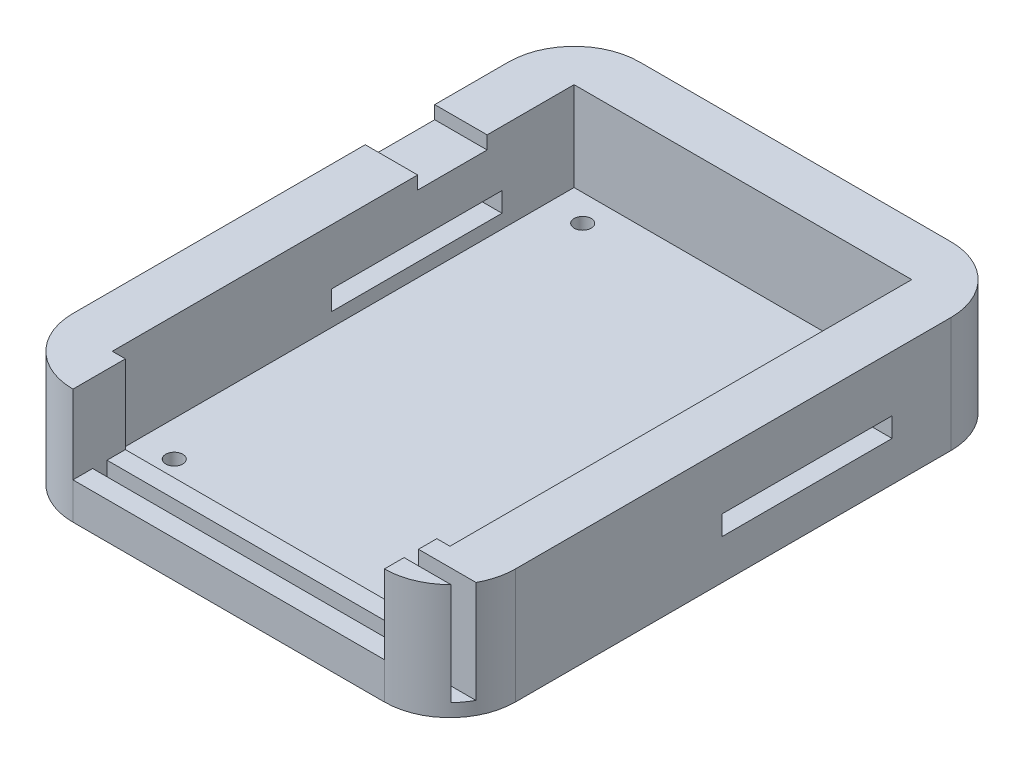
SolidWorks part; units mm, degrees
ref_plane "前视基准面" through (0, 0, 0) normal (0, 0, 1) x (1, 0, 0)
ref_plane "上视基准面" through (0, 0, 0) normal (0, 1, 0) x (1, 0, 0)
ref_plane "右视基准面" through (0, 0, 0) normal (1, 0, 0) x (0, 0, -1)
other "Configuration Table"
sketch "草图1" plane through (0, 0, 0) normal (0, 1, 0) x (1, 0, 0)
  line L0 (0, 0) -> (0, 48.9994) construction
  line L1 (-25.775, -35.25) -> (25.775, -35.25)
  line L2 (-25.775, -35.25) -> (-25.775, 35.25)
  line L3 (-25.775, 35.25) -> (25.775, 35.25)
  line L4 (25.775, -35.25) -> (25.775, 35.25)
  line L5 (-25.775, -35.25) -> (25.775, 35.25) construction
  line L6 (-25.775, 35.25) -> (25.775, -35.25) construction
  line L7 (0, 0) -> (56.532, 0) construction
  circle A0 centre (-20.3835, 31.1785) radius 1.3
  circle A1 centre (20.3835, 31.1785) radius 1.3
  circle A2 centre (20.3835, -31.1785) radius 1.3
  circle A3 centre (-20.3835, -31.1785) radius 1.3
  point P0 (0, 0)
  dimension "D5" = 2.6
  dimension "D1" = 51.55
  dimension "D2" = 70.5
  dimension "D3" = 40.767
  dimension "D4" = 62.357
extrude "凸台-拉伸1" add sketch "草图1" along normal blind 4
sketch "草图2" plane through (0, 0, 0) normal (0, -1, 0) x (1, 0, 0)
  line L0 (-25.775, 35.25) -> (25.775, 35.25) construction
  line L1 (25.775, 35.25) -> (25.775, -35.25) construction
  line L2 (25.775, -35.25) -> (-25.775, -35.25) construction
  line L3 (-25.775, -35.25) -> (-25.775, 35.25) construction
  line L4 (-25.775, 35.25) -> (25.775, 35.25)
  line L5 (25.775, 35.25) -> (25.775, -35.25)
  line L6 (25.775, -35.25) -> (-25.775, -35.25)
  line L7 (-25.775, -35.25) -> (-25.775, 35.25)
  line L9 (-23.775, 43.25) -> (23.775, 43.25)
  line L10 (-33.775, 33.25) -> (-33.775, -33.25)
  line L11 (-23.775, -43.25) -> (23.775, -43.25)
  line L12 (33.775, 33.25) -> (33.775, -33.25)
  line L13 (-33.775, 43.25) -> (33.775, -43.25) construction
  line L14 (-33.775, -43.25) -> (33.775, 43.25) construction
  arc A0 (-23.775, -43.25) -> (-33.775, -33.25) centre (-23.775, -33.25) cw
  arc A1 (23.775, -43.25) -> (33.775, -33.25) centre (23.775, -33.25) ccw
  arc A2 (33.775, 33.25) -> (23.775, 43.25) centre (23.775, 33.25) ccw
  arc A3 (-33.775, 33.25) -> (-23.775, 43.25) centre (-23.775, 33.25) cw
  point P2 (0, 0)
  dimension "D3" = 10
  dimension "D1" = 8
  dimension "D2" = 8
extrude "凸台-拉伸2" add sketch "草图2" against normal blind 17.6
sketch "草图4" plane through (0, 17.6, 0) normal (0, 1, 0) x (1, 0, 0)
  line L0 (25.775, -35.25) -> (-25.775, -35.25) construction
  line L1 (23.775, -43.25) -> (-23.775, -43.25)
  line L2 (23.775, -43.25) -> (23.775, -35.25)
  line L3 (23.775, -35.25) -> (-23.775, -35.25)
  line L4 (-23.775, -43.25) -> (-23.775, -35.25)
  line L5 (23.775, -43.25) -> (-23.775, -43.25) construction
extrude "切除-拉伸1" cut sketch "草图4" against normal blind 12
ref_plane "基准面1" through (0, 0, 38.05) normal (0, 0, -1) x (-1, 0, 0)
sketch "草图6" plane through (0, 0, 38.05) normal (0, 0, -1) x (-1, 0, 0)
  line L0 (25.775, 4) -> (-25.775, 4) construction
  line L1 (23.775, 17.6) -> (-33.775, 17.6)
  line L2 (23.775, 17.6) -> (23.775, 2)
  line L3 (23.775, 2) -> (-33.775, 2)
  line L4 (-33.775, 17.6) -> (-33.775, 2)
  line L5 (25.775, 4) -> (-25.775, 4) construction
  line L6 (23.775, 17.6) -> (23.775, 5.6) construction
  line L8 (-25.775, 17.6) -> (-23.775, 17.6) construction
  line L9 (-33.775, 17.6) -> (-33.775, 0) construction
  dimension "D1" = 2
extrude "切除-拉伸3" cut sketch "草图6" against normal blind 2.2
sketch "草图7" plane through (0, 17.6, 0) normal (0, 1, 0) x (1, 0, 0)
  line L0 (-25.775, -35.25) -> (-25.775, 35.25) construction
  line L1 (-25.775, 21.977) -> (-33.775, 21.977)
  line L2 (-25.775, 21.977) -> (-25.775, 11.3706)
  line L3 (-25.775, 11.3706) -> (-33.775, 11.3706)
  line L4 (-33.775, 21.977) -> (-33.775, 11.3706)
  line L5 (-33.775, -33.25) -> (-33.775, 33.25) construction
  line L6 (-25.775, 35.25) -> (25.775, 35.25) construction
  dimension "D1" = 13.273
  dimension "D2" = 23.8794
extrude "切除-拉伸4" cut sketch "草图7" against normal blind 2
sketch "草图8" plane through (-33.775, 0, 0) normal (-1, 0, 0) x (0, 0, 1)
  line L0 (-33.25, 17.6) -> (-33.25, 0) construction
  line L1 (-24.25, 9.1) -> (1.75, 9.1)
  line L2 (-24.25, 9.1) -> (-24.25, 6.1)
  line L3 (-24.25, 6.1) -> (1.75, 6.1)
  line L4 (1.75, 9.1) -> (1.75, 6.1)
  line L5 (33.25, 17.6) -> (-11.3706, 17.6) construction
  dimension "D1" = 9
  dimension "D2" = 26
  dimension "D3" = 3
  dimension "D4" = 8.5
extrude "切除-拉伸5" cut sketch "草图8" against normal blind 83
